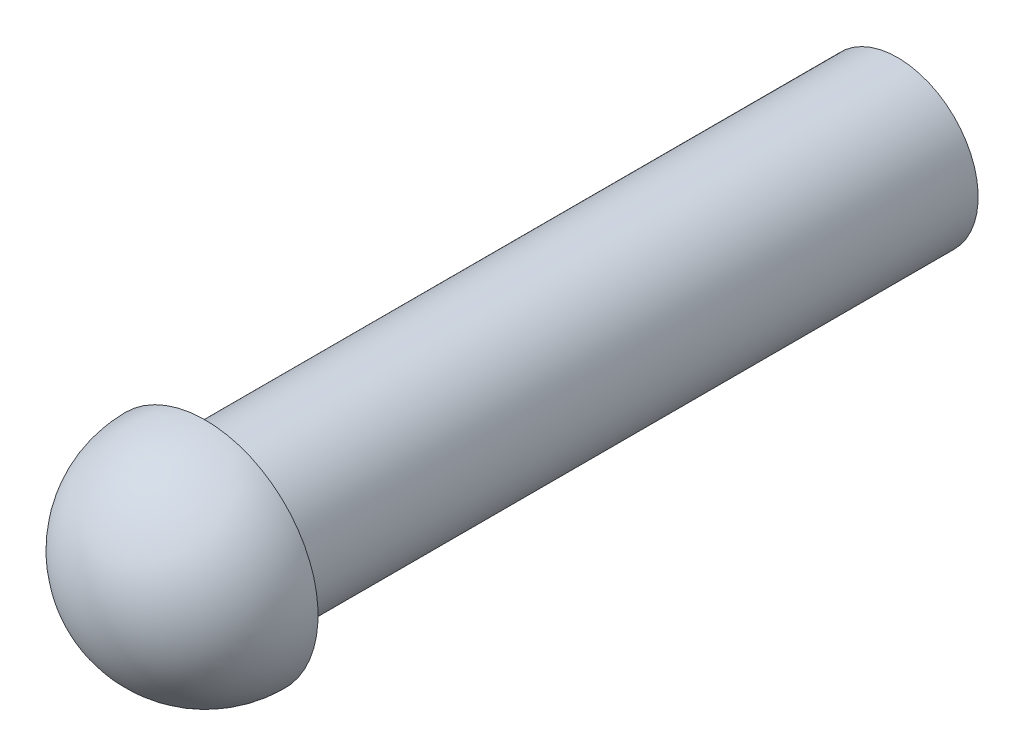
SolidWorks part; units mm, degrees
ref_plane "前视基准面" through (0, 0, 0) normal (0, 0, 1) x (1, 0, 0)
ref_plane "上视基准面" through (0, 0, 0) normal (0, 1, 0) x (1, 0, 0)
ref_plane "右视基准面" through (0, 0, 0) normal (1, 0, 0) x (0, 0, -1)
sketch "草图1" plane through (0, 0, 0) normal (0, 0, 1) x (1, 0, 0)
  line L0 (110, 90) -> (110, 82)
  line L1 (110, 82) -> (110, 98)
  circle A0 centre (110, 90) radius 8
revolve "旋转4" add sketch "草图1" angle 180 about L1
sketch "草图2" plane through (0, 120, 0) normal (0, 1, 0) x (1, 0, 0)
  line L0 (117.5341, -2.6904) -> (102.4659, -2.6904)
  line L1 (102.4659, -2.6904) -> (102.4659, -10.6561)
  line L2 (102.4659, -10.6561) -> (117.5341, -10.6561)
  line L3 (117.5341, -10.6561) -> (117.5341, -2.6904)
  arc A0 (102, 0) -> (118, 0) centre (110, 0) ccw construction
extrude "切除-拉伸1" cut sketch "草图2" against normal blind 56
sketch "草图3" plane through (0, 0, 0) normal (0, 0, -1) x (-1, 0, 0)
  circle A0 centre (-117.9622, 79.2774) radius 5
extrude "凸台-拉伸2" add sketch "草图3" along normal blind 43
sketch "草图19" plane through (0, 0, -43) normal (0, 0, -1) x (-1, 0, 0)
  circle A0 centre (-117.9622, 79.2774) radius 4.6
sketch "草图45" plane through (0, 0, 0) normal (0, 0, -1) x (-1, 0, 0)
  circle A2 centre (-110, 90) radius 8
  circle A3 centre (-110, 90) radius 8
  dimension "D1" = 0
extrude "切除-拉伸2" cut sketch "草图45" against normal blind 10
sketch "草图46" plane through (0, 0, 0) normal (0, 0, 1) x (1, 0, 0)
  line L0 (117.9622, 79.2774) -> (117.9622, 86.2774)
  line L1 (117.9622, 86.2774) -> (117.9622, 72.2774)
  circle A0 centre (117.9622, 79.2774) radius 7
revolve "旋转5" add sketch "草图46" angle 180 about L1
sketch3d "3D草图3"
  point P0 (118.2923, 72.5862, 2.0296)
ref_plane "基准面10" through (0, 72.5862, 0) normal (0, -1, 0) x (-1, 0, 0)
